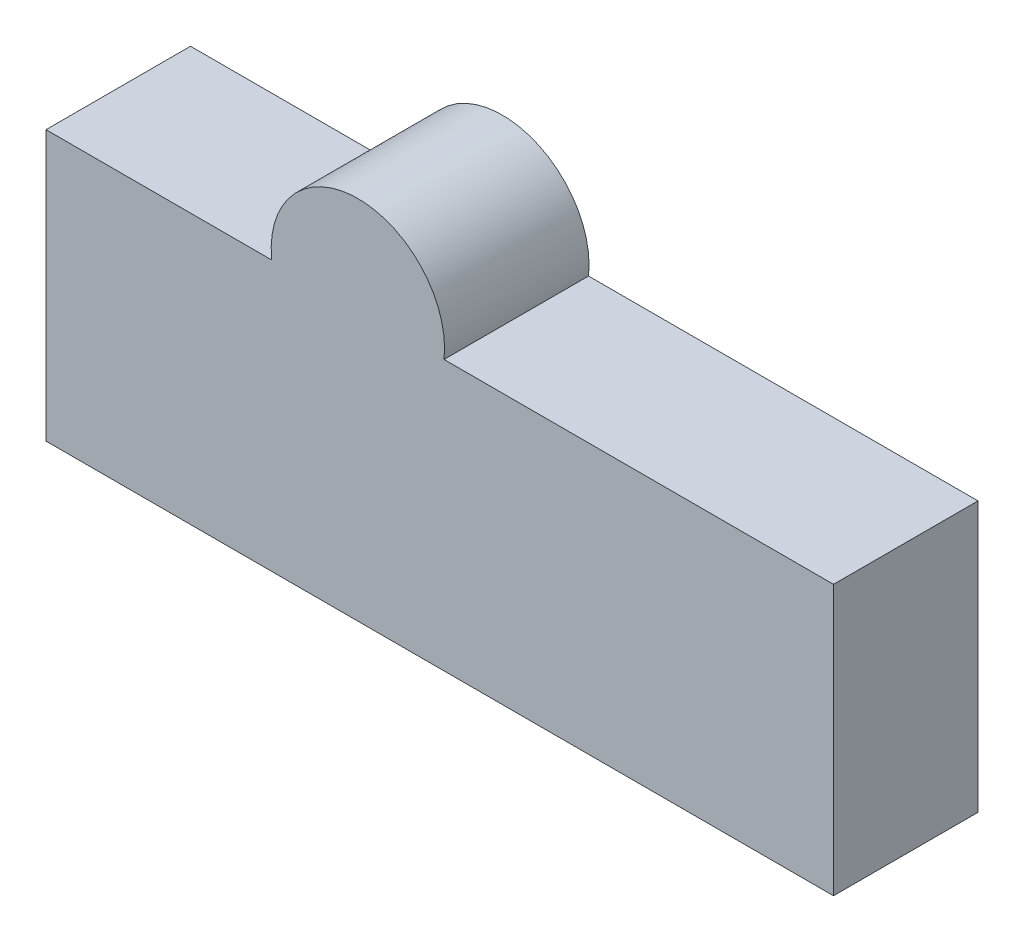
SolidWorks part; units mm, degrees
ref_plane "Front Plane" through (0, 0, 0) normal (0, 0, 1) x (1, 0, 0)
ref_plane "Top Plane" through (0, 0, 0) normal (0, 1, 0) x (1, 0, 0)
ref_plane "Right Plane" through (0, 0, 0) normal (1, 0, 0) x (0, 0, -1)
sketch "Sketch1" plane through (0, 0, 0) normal (0, 0, 1) x (1, 0, 0)
  line L33 (11.425, -5.1538) -> (13.7681, -5.1538)
  line L34 (11.425, -7.9538) -> (11.425, -5.1538)
  line L35 (15.5569, -5.1538) -> (19.6, -5.1538)
  line L36 (19.6, -7.9538) -> (11.425, -7.9538)
  line L37 (11.425, -5.1538) -> (13.7681, -5.1538)
  line L38 (11.425, -7.9538) -> (11.425, -5.1538)
  line L39 (15.5569, -5.1538) -> (19.6, -5.1538)
  line L40 (19.6, -7.9538) -> (11.425, -7.9538)
  line L41 (19.6, -5.1538) -> (19.6, -7.9538)
  arc A2 (15.5569, -5.1538) -> (13.7681, -5.1538) centre (14.6625, -5.0538) ccw
  arc A3 (15.5569, -5.1538) -> (13.7681, -5.1538) centre (14.6625, -5.0538) ccw
  dimension "D1" = 0.1
extrude "Boss-Extrude1" add sketch "Sketch1" along normal up to surface (1.5 mm away)
